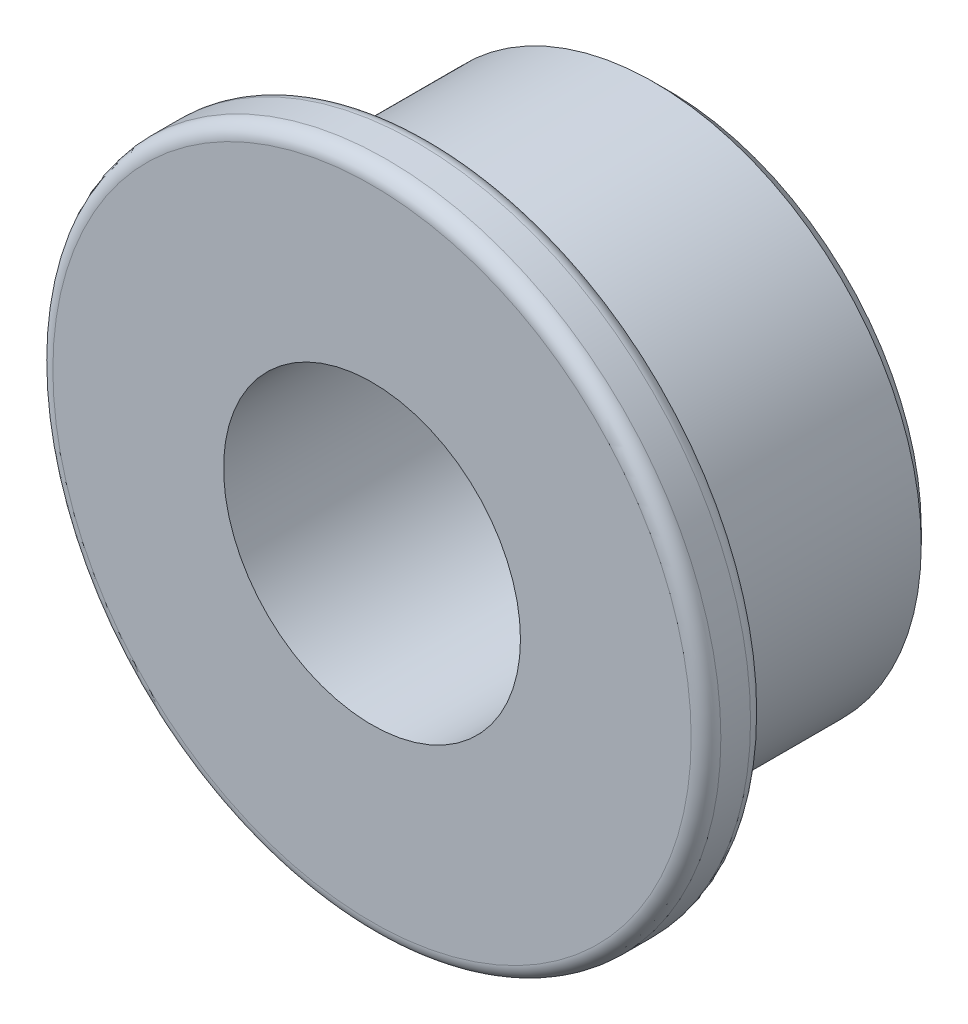
SolidWorks part; units mm, degrees
ref_plane "Front Plane" through (0, 0, 0) normal (0, 0, 1) x (1, 0, 0)
ref_plane "Top Plane" through (0, 0, 0) normal (0, 1, 0) x (1, 0, 0)
ref_plane "Right Plane" through (0, 0, 0) normal (1, 0, 0) x (0, 0, -1)
sketch "Sketch1" plane through (0, 0, 0) normal (0, 0, 1) x (1, 0, 0)
  circle A0 centre (0, 0) radius 9
  circle A1 centre (0, 0) radius 5
  dimension "D1" = 18
  dimension "D2" = 10
extrude "Boss-Extrude1" add sketch "Sketch1" against normal blind 8
sketch "Sketch2" plane through (0, 0, 0) normal (0, 0, 1) x (1, 0, 0)
  circle A0 centre (0, 0) radius 11.25
  circle A1 centre (0, 0) radius 5
  circle A2 centre (0, 0) radius 5 construction
  dimension "D1" = 22.5
extrude "Boss-Extrude2" add sketch "Sketch2" along normal blind 2
fillet "Fillet1" radius 0.5 1 edges at (11.25, 0, 2)
fillet "Fillet2" radius 0.5 1 edges at (11.25, 0, 0)
fillet "Fillet3" radius 0.8 1 edges at (9, 0, 0)
chamfer "Chamfer1" distance 0.5 angle 45 1 edges at (9, 0, -8)
